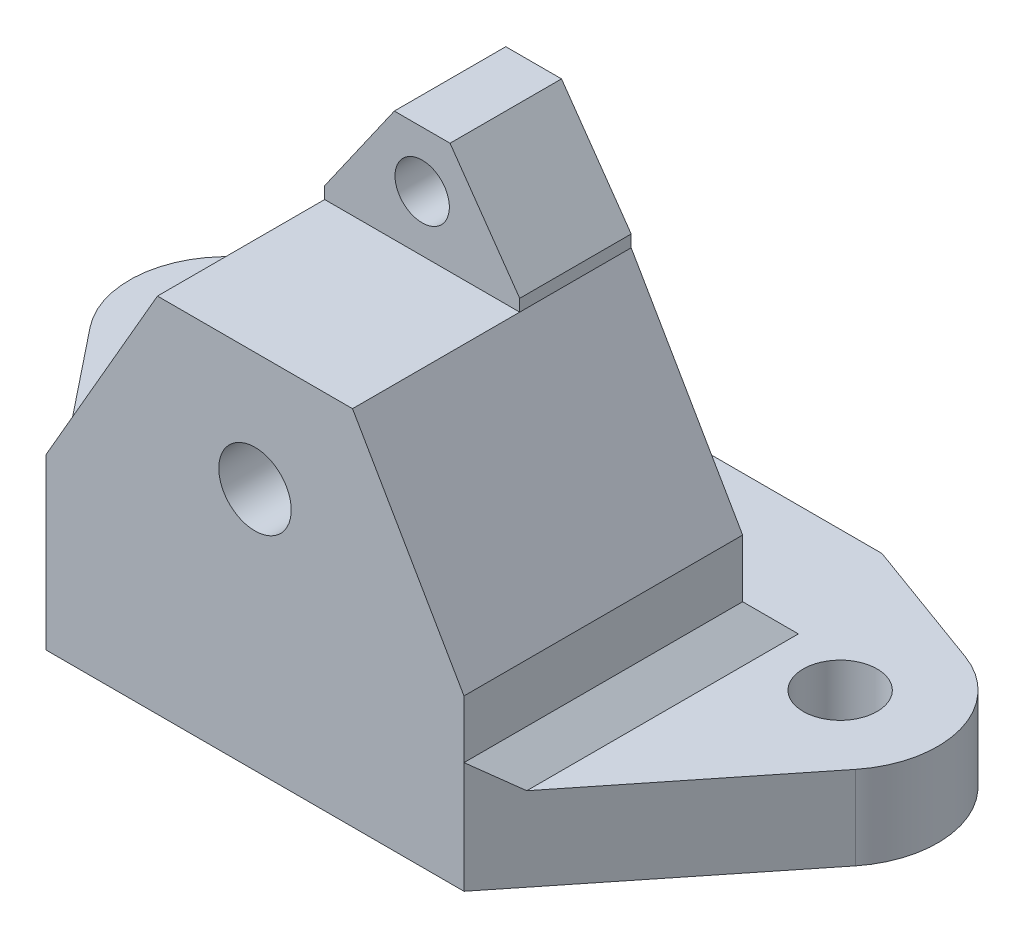
SolidWorks part; units mm, degrees
ref_plane "Front Plane" through (0, 0, 0) normal (0, 0, 1) x (1, 0, 0)
ref_plane "Top Plane" through (0, 0, 0) normal (0, 1, 0) x (1, 0, 0)
ref_plane "Right Plane" through (0, 0, 0) normal (1, 0, 0) x (0, 0, -1)
sketch "Sketch1" plane through (0, 0, 0) normal (0, 0, 1) x (1, 0, 0)
  line L1 (-15, 13) -> (15, 13)
  line L2 (-15, 13) -> (-15, -13)
  line L3 (-15, -13) -> (15, -13)
  line L4 (15, 13) -> (15, -13)
  line L5 (-15, 13) -> (15, -13) construction
  line L6 (-15, -13) -> (15, 13) construction
  point P0 (0, 0)
  dimension "D1" = 26
  dimension "D2" = 30
extrude "Boss-Extrude1" add sketch "Sketch1" along normal blind 30
sketch "Sketch2" plane through (0, 0, 0) normal (0, 0, 1) x (1, 0, 0)
  line L2 (0, -16.5) -> (0, 16.5) construction
  line L3 (16.5, 0) -> (-16.5, 0) construction
  circle A0 centre (0, 5) radius 5.25
  dimension "D1" = 10.5
  dimension "D2" = 5
extrude "Cut-Extrude1" cut sketch "Sketch2" along normal blind 15
sketch "Sketch3" plane through (0, 0, 0) normal (0, 0, 1) x (1, 0, 0)
  line L0 (16.5, 0) -> (-16.5, 0) construction
  line L1 (0, -14.3) -> (0, 14.3) construction
  circle A0 centre (0, 4.5) radius 2.6
  dimension "D1" = 5.2
  dimension "D2" = 4.5
extrude "Cut-Extrude2" cut sketch "Sketch3" along normal up to next
sketch "Sketch4" plane through (0, -13, 0) normal (0, -1, 0) x (1, 0, 0)
  line L0 (-22, 10) -> (34.0128, 10) construction
  line L1 (18.7, 0) -> (-18.7, 0) construction
  line L2 (0, -1.0234) -> (0, 38.56) construction
  line L3 (0, -16.5) -> (0, 16.5) construction
  line L4 (-15, 30) -> (-27.4722, 14.3653)
  line L5 (-15, 0) -> (-24.396, 3.4228)
  line L6 (-15, 30) -> (-15, 0) construction
  line L7 (15, 0) -> (24.396, 3.4228)
  line L8 (15, 30) -> (27.4722, 14.3653)
  line L9 (-15, 30) -> (-15, 0)
  line L10 (15, 30) -> (15, 0)
  arc A0 (-27.4722, 14.3653) -> (-24.396, 3.4228) centre (-22, 10) ccw
  circle A1 centre (-22, 10) radius 2.65
  circle A2 centre (22, 10) radius 2.65
  arc A3 (27.4722, 14.3653) -> (24.396, 3.4228) centre (22, 10) cw
  dimension "D3" = 7
  dimension "D4" = 5.3
  dimension "D1" = 10
  dimension "D2" = 22
extrude "Boss-Extrude2" add sketch "Sketch4" against normal blind 6
chamfer "Chamfer1" distance 8 angle 60 2 edges at (-15, 13, 15) (15, 13, 15)
sketch "Sketch5" plane through (0, 0, 0) normal (1, 0, 0) x (0, 0, -1)
  line L0 (-30, 13) -> (0, 13) construction
  line L1 (-10, 13) -> (0, 13)
  line L2 (-10, 13) -> (-10, -7)
  line L3 (-10, -7) -> (0, -7)
  line L4 (0, 13) -> (0, -7)
  line L5 (0, 18.7) -> (0, -18.7) construction
  line L7 (0, -7) -> (-3.4228, -7) construction
  dimension "D1" = 10
extrude "Cut-Extrude3" cut sketch "Sketch5" against normal mid plane 40
chamfer "Chamfer2" distance 2 angle 45 3 edges at (0, -7, 10)
sketch "Sketch6" plane through (0, 0, 10) normal (0, 0, -1) x (-1, 0, 0)
  line L0 (-7, 13) -> (-7, 21)
  line L1 (-7, 21) -> (7, 21)
  line L2 (7, 21) -> (7, 13)
  line L3 (7, 13) -> (-7, 13)
  circle A0 centre (0, 17) radius 1.95
  dimension "D2" = 3.9
  dimension "D1" = 8
  dimension "D3" = 4
  dimension "D4" = 7
extrude "Boss-Extrude3" add sketch "Sketch6" against normal blind 8
chamfer "Chamfer3" distance 5 angle 55 2 edges at (7, 21, 14) (-7, 21, 14)
